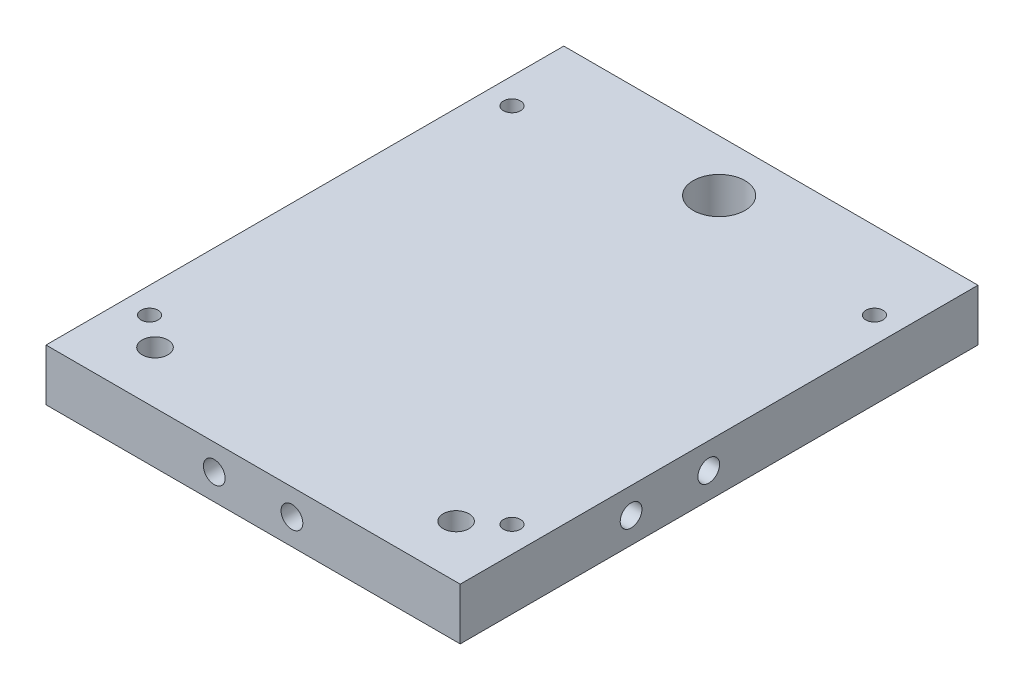
SolidWorks part; units mm, degrees
material "6061"
ref_plane "前视" through (0, 0, 0) normal (0, 0, 1) x (1, 0, 0)
ref_plane "上视" through (0, 0, 0) normal (0, 1, 0) x (1, 0, 0)
ref_plane "右视" through (0, 0, 0) normal (1, 0, 0) x (0, 0, -1)
sketch "草图1" plane through (0, 0, 0) normal (0, 1, 0) x (1, 0, 0)
  line L1 (-40, -50) -> (40, -50)
  line L2 (-40, -50) -> (-40, 50)
  line L3 (-40, 50) -> (40, 50)
  line L4 (40, -50) -> (40, 50)
  line L5 (-40, -50) -> (40, 50) construction
  line L6 (-40, 50) -> (40, -50) construction
  point P0 (0, 0)
  dimension "D1" = 80
  dimension "D2" = 100
extrude "凸台-拉伸1" add sketch "草图1" along normal blind 10
hole_wizard "孔1" positions "草图3" profile "草图2" legacy end condition through all
sketch "草图3" plane through (0, 10, 0) normal (0, 1, 0) x (1, 0, 0)
  line L0 (0, 50) -> (0, 26.7205) construction
  line L1 (40, 50) -> (-40, 50) construction
  point P0 (0, 40)
  dimension "D1" = 10
sketch "草图2" plane through (0, 10, -40) normal (1, 0, 0) x (0, 0, 1)
  line L0 (0, 0) -> (0, 10)
  line L1 (0, 10) -> (5, 10)
  line L2 (5, 10) -> (5, 0)
  line L3 (5, 0) -> (0, 0)
  line L4 (0, 110) -> (0, -10) construction
  dimension "直径" = 10
  dimension "深度" = 10
hole_wizard "M4 螺纹孔1" positions "草图5" profile "草图4" tap size "M4" standard "Gb" end condition through all
sketch "草图5" plane through (0, 0, 0) normal (0, -1, 0) x (-1, 0, 0)
  line L0 (40, 0) -> (-32.7878, 0) construction
  line L1 (40, 50) -> (40, -50) construction
  line L2 (0, -50) -> (0, -16.9902) construction
  line L3 (40, -50) -> (-40, -50) construction
  point P0 (35, -35)
  point P2 (-35, -35)
  point P12 (-35, 35)
  point P13 (35, 35)
  dimension "D1" = 70
  dimension "D3" = 70
sketch "草图4" plane through (-35, 0, 35) normal (1, 0, 0) x (0, 0, -1)
  line L0 (0, 0) -> (0, 10)
  line L1 (0, 10) -> (1.65, 10)
  line L2 (1.65, 10) -> (1.65, 0)
  line L5 (1.65, 0) -> (0, 0)
  line L11 (0, -6.35) -> (0, 107.95) construction
  dimension "通孔螺纹孔钻头直径" = 3.3
  dimension "通孔螺纹孔钻头深度" = 10
cosmetic thread "孔螺蚊线1"
cosmetic thread "孔螺蚊线2"
cosmetic thread "孔螺蚊线3"
cosmetic thread "孔螺蚊线4"
hole_wizard "M6 螺纹孔1" positions "草图8" profile "草图7" tap size "M6" standard "Gb" end condition through all
sketch "草图8" plane through (0, 10, 0) normal (0, 1, 0) x (1, 0, 0)
  line L0 (0, 40) -> (0, -66.9682) construction
  line L1 (0, 40) -> (-29.0717, -39.8739) construction
  circle A0 centre (0, 40) radius 85 construction
  point P0 (-29.0717, -39.8739)
  point P8 (29.0717, -39.8739)
  dimension "D1" = 170
  dimension "D2" = 20
sketch "草图7" plane through (-29.0717, 10, 39.8739) normal (1, 0, 0) x (0, 0, 1)
  line L0 (0, 0) -> (0, 10)
  line L1 (0, 10) -> (2.5, 10)
  line L2 (2.5, 10) -> (2.5, 0)
  line L5 (2.5, 0) -> (0, 0)
  line L11 (0, -6.35) -> (0, 107.95) construction
  dimension "通孔螺纹孔钻头直径" = 5
  dimension "通孔螺纹孔钻头深度" = 10
cosmetic thread "孔螺蚊线5"
cosmetic thread "孔螺蚊线6"
hole_wizard "M5 螺纹孔1" positions "草图11" profile "草图10" tap size "M5" standard "Gb"
sketch "草图11" plane through (40, 0, 0) normal (1, 0, 0) x (0, 0, -1)
  line L0 (-50, 5) -> (-17, 5) construction
  line L1 (-50, 10) -> (-50, 0) construction
  point P0 (-17, 5)
  point P2 (-2, 5)
  dimension "D1" = 15
  dimension "D2" = 33
sketch "草图10" plane through (40, 5, 17) normal (0, 1, 0) x (0, 0, -1)
  line L0 (0, 0) -> (0, 13.6618)
  line L1 (0, 13.6618) -> (2.1, 12.4)
  line L2 (2.1, 12.4) -> (2.1, 0)
  line L5 (2.1, 0) -> (0, 0)
  line L10 (0, 13.6618) -> (-2.1, 12.4) construction
  line L11 (0, -6.35) -> (0, 107.95) construction
  dimension "螺纹孔钻头直径" = 4.2
  dimension "螺纹孔钻头深度" = 12.4
  dimension "导头角度" = 118
cosmetic thread "孔螺蚊线7"
cosmetic thread "孔螺蚊线8"
hole_wizard "M5 螺纹孔2" positions "草图13" profile "草图12" tap size "M5" standard "Gb"
sketch "草图13" plane through (-40, 0, 0) normal (-1, 0, 0) x (0, 0, 1)
  line L0 (50, 10) -> (50, 0) construction
  point P0 (5, 5)
  point P2 (-8, 5)
  dimension "D1" = 13
  dimension "D2" = 45
sketch "草图12" plane through (-40, 5, 5) normal (0, 1, 0) x (0, 0, 1)
  line L0 (0, 0) -> (0, 13.6618)
  line L1 (0, 13.6618) -> (2.1, 12.4)
  line L2 (2.1, 12.4) -> (2.1, 0)
  line L5 (2.1, 0) -> (0, 0)
  line L10 (0, 13.6618) -> (-2.1, 12.4) construction
  line L11 (0, -6.35) -> (0, 107.95) construction
  dimension "螺纹孔钻头直径" = 4.2
  dimension "螺纹孔钻头深度" = 12.4
  dimension "导头角度" = 118
cosmetic thread "孔螺蚊线9"
cosmetic thread "孔螺蚊线10"
hole_wizard "M5 螺纹孔3" positions "草图15" profile "草图14" tap size "M5" standard "Gb"
sketch "草图15" plane through (0, 0, 50) normal (0, 0, 1) x (1, 0, 0)
  line L0 (-40, 5) -> (0, 5) construction
  line L1 (-40, 10) -> (-40, 0) construction
  line L2 (0, 5) -> (0, 10) construction
  line L3 (-40, 10) -> (40, 10) construction
  point P0 (-7.5, 5)
  point P15 (7.5, 5)
  dimension "D1" = 15
sketch "草图14" plane through (-7.5, 5, 50) normal (1, 0, 0) x (0, -1, 0)
  line L0 (0, 0) -> (0, 11.6618)
  line L1 (0, 11.6618) -> (2.1, 10.4)
  line L2 (2.1, 10.4) -> (2.1, 0)
  line L5 (2.1, 0) -> (0, 0)
  line L10 (0, 11.6618) -> (-2.1, 10.4) construction
  line L11 (0, -6.35) -> (0, 107.95) construction
  dimension "螺纹孔钻头直径" = 4.2
  dimension "螺纹孔钻头深度" = 10.4
  dimension "导头角度" = 118
cosmetic thread "孔螺蚊线11"
cosmetic thread "孔螺蚊线12"
